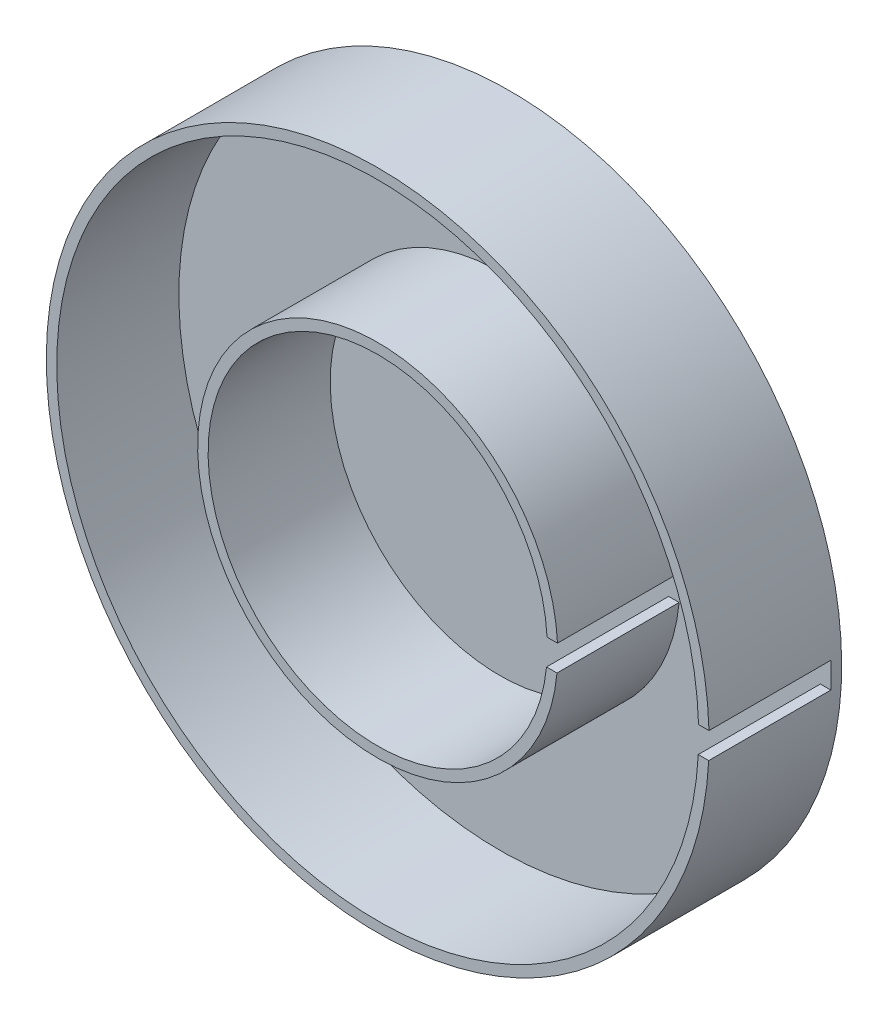
SolidWorks part; units mm, degrees
ref_plane "Front Plane" through (0, 0, 0) normal (1, 0, 0) x (0, 1, 0)
ref_plane "Top Plane" through (0, 0, 0) normal (0, 0, 1) x (0, 1, 0)
ref_plane "Right Plane" through (0, 0, 0) normal (0, 1, 0) x (-1, 0, 0)
sketch "Sketch2" plane through (0, 0, 0) normal (0, 0, 1) x (0, 1, 0)
  circle A0 centre (0, 0) radius 63.5
  dimension "D1" = 127
extrude "Boss-Extrude1" add sketch "Sketch2" along normal blind 25.4
shell "Shell1" thickness 2
sketch "Sketch3" plane through (0, 0, 2) normal (0, 0, 1) x (1, 0, 0)
  line L0 (32.4495, 1.811) -> (34.4524, 1.811)
  line L1 (32.3432, -3.189) -> (34.3523, -3.189)
  arc A0 (32.4495, 1.811) -> (32.3432, -3.189) centre (0, 0) ccw
  arc A1 (34.4524, 1.811) -> (34.3523, -3.189) centre (0, 0) ccw
  circle A2 centre (0, 0) radius 34.5 construction
  circle A3 centre (0, 0) radius 32.5 construction
  dimension "D1" = 65
  dimension "D3" = 5
  dimension "D2" = 2
extrude "Boss-Extrude2" add sketch "Sketch3" along normal up to surface (23.4 mm away) up to face at (61.5, 0, 25.4)
sketch "Sketch4" plane through (0, 0, 25.4) normal (0, 0, 1) x (1, 0, 0)
  line L0 (34.3523, -3.189) -> (63.4199, -3.189)
  line L1 (34.4524, 1.811) -> (63.4742, 1.811)
  line L2 (34.4524, 1.811) -> (34.3523, -3.189)
  line L3 (63.4199, -3.189) -> (70.0822, -0.689)
  line L4 (70.0822, -0.689) -> (63.4742, 1.811)
  circle A0 centre (0, 0) radius 63.5 construction
extrude "Cut-Extrude2" cut sketch "Sketch4" against normal up to surface (23.4 mm away) up to face at (61.5, 0, 2)
